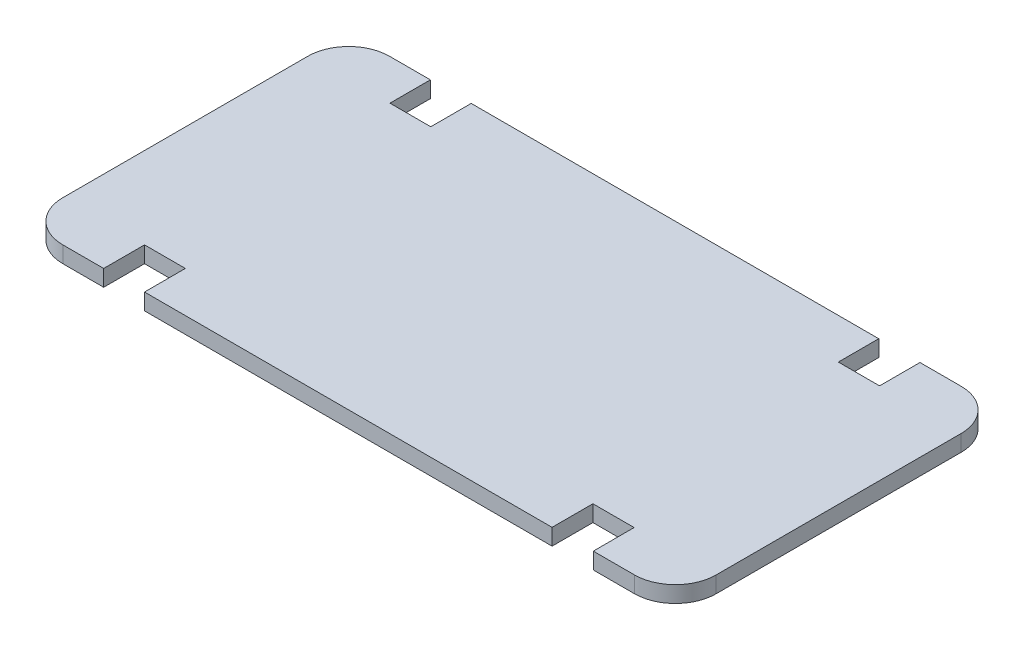
SolidWorks part; units mm, degrees
ref_plane "Front Plane" through (0, 0, 0) normal (0, 0, 1) x (1, 0, 0)
ref_plane "Top Plane" through (0, 0, 0) normal (0, 1, 0) x (1, 0, 0)
ref_plane "Right Plane" through (0, 0, 0) normal (1, 0, 0) x (0, 0, -1)
sketch "Sketch2" plane through (0, 0, 0) normal (0, 1, 0) x (1, 0, 0)
  line L1 (-88.9, -50.8) -> (88.9, -50.8)
  line L2 (-101.6, -38.1) -> (-101.6, 38.1)
  line L3 (-88.9, 50.8) -> (88.9, 50.8)
  line L4 (101.6, -38.1) -> (101.6, 38.1)
  line L5 (-101.6, -50.8) -> (101.6, 50.8) construction
  line L6 (-101.6, 50.8) -> (101.6, -50.8) construction
  arc A0 (-88.9, -50.8) -> (-101.6, -38.1) centre (-88.9, -38.1) cw
  arc A1 (-101.6, 38.1) -> (-88.9, 50.8) centre (-88.9, 38.1) cw
  arc A2 (88.9, 50.8) -> (101.6, 38.1) centre (88.9, 38.1) cw
  arc A3 (88.9, -50.8) -> (101.6, -38.1) centre (88.9, -38.1) ccw
  point P1 (0, 0)
  dimension "D3" = 12.7
  dimension "D1" = 203.2
  dimension "D2" = 101.6
extrude "Boss-Extrude1" add sketch "Sketch2" along normal blind 5.08
sketch "Sketch3" plane through (0, 5.08, 0) normal (0, 1, 0) x (1, 0, 0)
  line L1 (-88.9, -50.8) -> (88.9, -50.8) construction
  line L2 (-76.1887, -50.8) -> (-76.1887, -38.1)
  line L3 (-76.1887, -38.1) -> (-63.4887, -38.1)
  line L4 (-63.4887, -38.1) -> (-63.4887, -50.8)
  line L5 (-63.4887, -50.8) -> (-76.1887, -50.8)
  line L6 (88.9, 50.8) -> (-88.9, 50.8) construction
  line L7 (-76.1887, 50.8) -> (-63.4887, 50.8)
  line L8 (-63.4887, 50.8) -> (-63.4887, 38.2246)
  line L9 (-63.4887, 38.2246) -> (-76.1887, 38.2246)
  line L10 (-76.1887, 38.2246) -> (-76.1887, 50.8)
  line L11 (76.0845, -50.8) -> (76.0845, -38.1)
  line L12 (76.0845, -38.1) -> (63.2623, -38.1)
  line L13 (63.2623, -38.1) -> (63.2623, -50.8)
  line L14 (63.2623, -50.8) -> (76.0845, -50.8)
  line L15 (76.0845, 50.8) -> (76.0845, 38.2246)
  line L16 (76.0845, 38.2246) -> (63.2623, 38.2246)
  line L17 (63.2623, 38.2246) -> (63.2623, 50.8)
  line L18 (63.2623, 50.8) -> (76.0845, 50.8)
  dimension "D1" = 12.7
  dimension "D2" = 12.7
extrude "Cut-Extrude1" cut sketch "Sketch3" against normal through all
